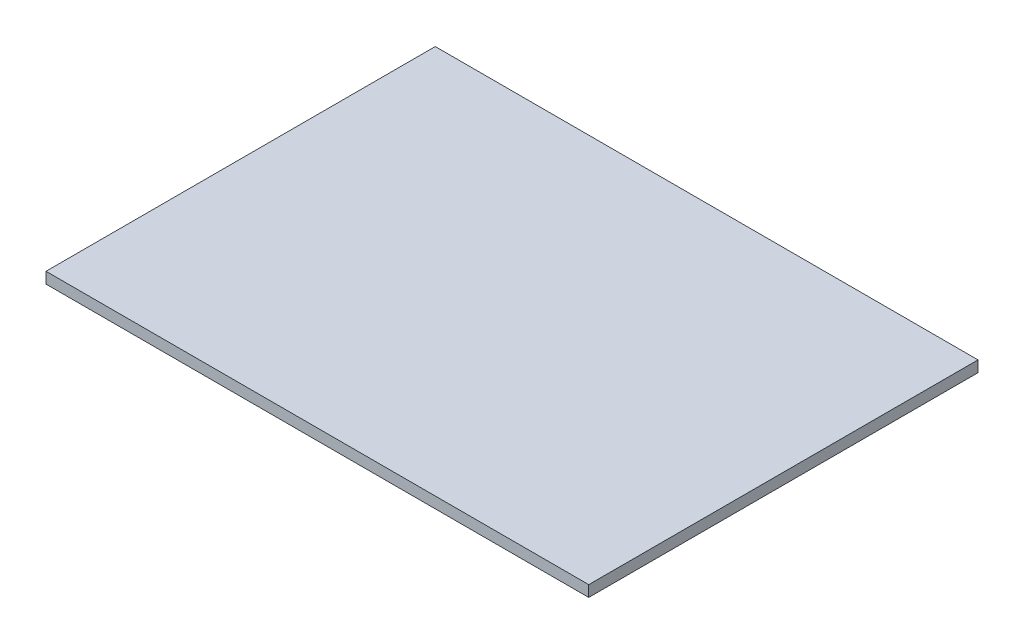
SolidWorks part; units mm, degrees
ref_plane "前视基准面" through (0, 0, 0) normal (0, 0, 1) x (1, 0, 0)
ref_plane "上视基准面" through (0, 0, 0) normal (0, 1, 0) x (1, 0, 0)
ref_plane "右视基准面" through (0, 0, 0) normal (1, 0, 0) x (0, 0, -1)
sketch "草图1" plane through (0, 0, 0) normal (0, 1, 0) x (1, 0, 0)
  line L1 (0, 0) -> (244, 0)
  line L2 (0, 0) -> (0, -175)
  line L3 (0, -175) -> (244, -175)
  line L4 (244, 0) -> (244, -175)
  dimension "D1" = 244
  dimension "D2" = 175
extrude "凸台-拉伸1" add sketch "草图1" along normal blind 5
